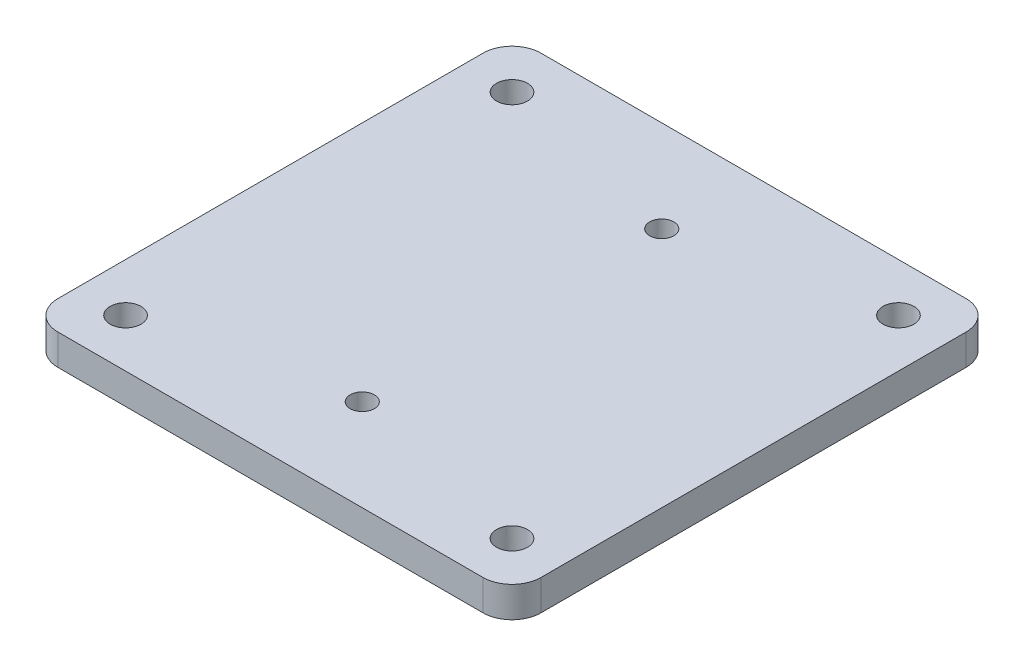
SolidWorks part; units mm, degrees
ref_plane "Front Plane" through (0, 0, 0) normal (0, 0, 1) x (1, 0, 0)
ref_plane "Top Plane" through (0, 0, 0) normal (0, 1, 0) x (1, 0, 0)
ref_plane "Right Plane" through (0, 0, 0) normal (1, 0, 0) x (0, 0, -1)
sketch "Sketch1" plane through (0, 0, 0) normal (0, 1, 0) x (1, 0, 0)
  line L0 (-15.5, 0) -> (15.5, 0) construction
  line L1 (-25, -25) -> (25, -25)
  line L2 (-25, -25) -> (-25, 25)
  line L3 (-25, 25) -> (25, 25)
  line L4 (25, -25) -> (25, 25)
  line L5 (-25, -25) -> (25, 25) construction
  line L6 (-25, 25) -> (25, -25) construction
  line L7 (0, -15.5) -> (0, 15.5) construction
  line L8 (-20, -20) -> (20, -20) construction
  line L9 (-20, -20) -> (-20, 20) construction
  line L10 (-20, 20) -> (20, 20) construction
  line L11 (20, -20) -> (20, 20) construction
  line L12 (-20, -20) -> (20, 20) construction
  line L13 (-20, 20) -> (20, -20) construction
  point P0 (0, 0)
  point P6 (0, 0)
  point P9 (0, 0)
  point P17 (0, 0)
  dimension "D1" = 31
  dimension "D2" = 50
  dimension "D3" = 50
  dimension "D4" = 40
  dimension "D5" = 40
  dimension "D6" = 31
extrude "Boss-Extrude1" add sketch "Sketch1" along normal blind 3.175
hole_wizard "M3 Clearance Hole1" positions "Sketch2" profile "Sketch3" hole size "M3" standard "ANSI Metric"
sketch "Sketch2" plane through (0, 3.175, 0) normal (0, 1, 0) x (1, 0, 0)
  point P0 (-20, 20)
  point P3 (20, 20)
  point P6 (-20, -20)
  point P9 (20, -20)
sketch "Sketch3" plane through (-20, 3.175, -20) normal (1, 0, 0) x (0, 0, 1)
  line L0 (0, 0) -> (0, 13.3614)
  line L1 (0, 13.3614) -> (1.6, 12.4)
  line L2 (1.6, 12.4) -> (1.6, 0)
  line L5 (1.6, 0) -> (0, 0)
  line L10 (0, 13.3614) -> (-1.6, 12.4) construction
  line L11 (0, -6.35) -> (0, 107.95) construction
  dimension "Hole Dia." = 3.2
  dimension "Hole Depth" = 12.4
  dimension "Drill Angle" = 118
hole_wizard "M3x0.5 Tapped Hole1" positions "Sketch4" profile "Sketch5" tap size "M3x0.5" standard "ANSI Metric" end condition through all
sketch "Sketch4" plane through (0, 3.175, 0) normal (0, 1, 0) x (1, 0, 0)
  point P0 (0, 15.5)
  point P3 (0, -15.5)
sketch "Sketch5" plane through (0, 3.175, -15.5) normal (1, 0, 0) x (0, 0, 1)
  line L0 (0, 0) -> (0, 3.175)
  line L1 (0, 3.175) -> (1.25, 3.175)
  line L2 (1.25, 3.175) -> (1.25, 0)
  line L5 (1.25, 0) -> (0, 0)
  line L11 (0, -6.35) -> (0, 107.95) construction
  dimension "Thru Tap Drill Dia." = 2.5
  dimension "Thru Tap Drill Depth" = 3.175
fillet "Fillet1" radius 3 4 edges at (25, 1.5875, 25) (-25, 1.5875, 25) (25, 1.5875, -25) (-25, 1.5875, -25)
